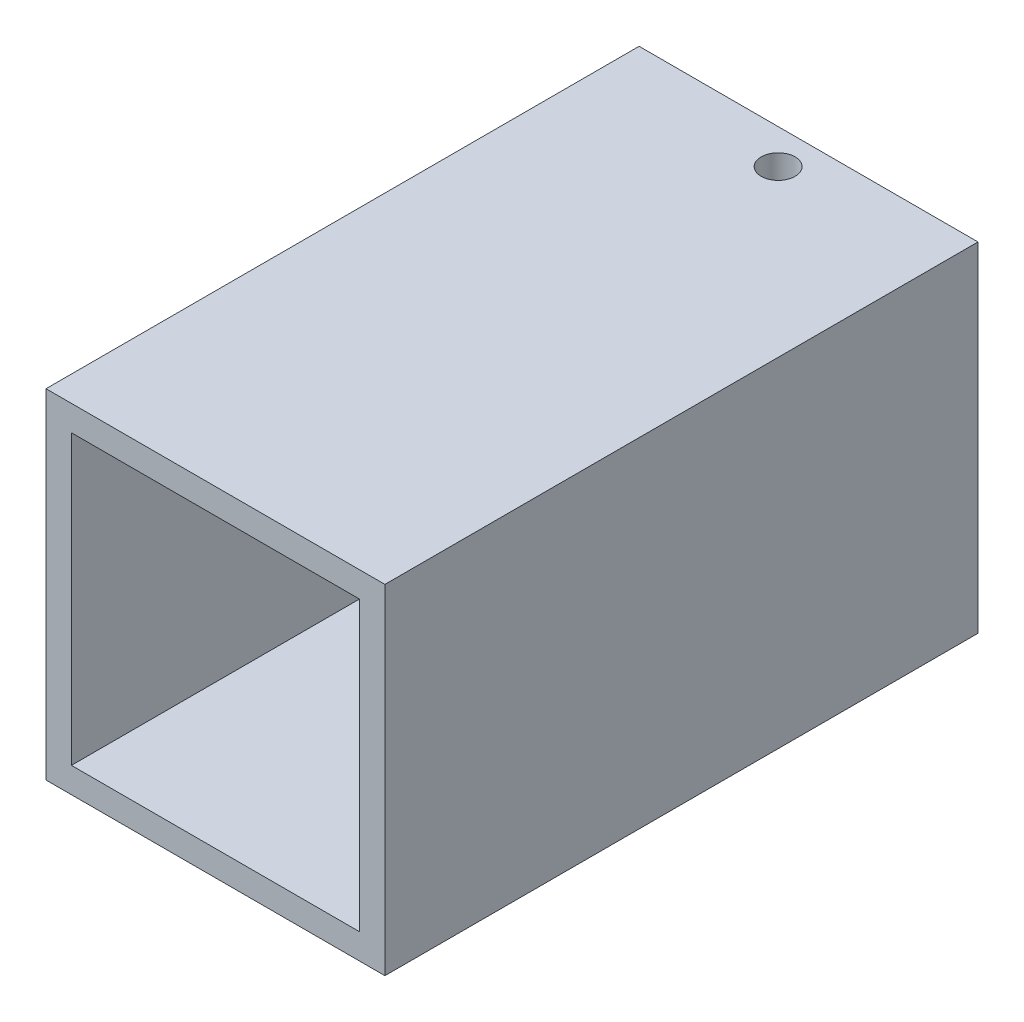
SolidWorks part; units mm, degrees
ref_plane "Płaszczyzna przednia" through (0, 0, 0) normal (0, 0, 1) x (1, 0, 0)
ref_plane "Płaszczyzna górna" through (0, 0, 0) normal (0, 1, 0) x (1, 0, 0)
ref_plane "Płaszczyzna prawa" through (0, 0, 0) normal (1, 0, 0) x (0, 0, -1)
sketch "Szkic1" plane through (0, 0, 0) normal (0, 0, 1) x (1, 0, 0)
  line L2 (-30.423, 18.5) -> (-30.423, -1.5)
  line L3 (-30.423, -1.5) -> (-10.423, -1.5)
  line L4 (-10.423, 18.5) -> (-10.423, -1.5)
  line L8 (-30.423, 18.5) -> (-10.423, 18.5)
  line L10 (-28.923, 17) -> (-11.923, 17)
  line L11 (-28.923, 17) -> (-28.923, 0)
  line L12 (-28.923, 0) -> (-11.923, 0)
  line L13 (-11.923, 17) -> (-11.923, 0)
  dimension "D1" = 20
  dimension "D2" = 20
  dimension "D3" = 1.5
  dimension "D4" = 1.5
  dimension "D5" = 1.5
  dimension "D6" = 1.5
extrude "Dodanie-wyciągnięcie1" add sketch "Szkic1" along normal blind 35
sketch "Szkic3" plane through (0, 18.5, 0) normal (0, 1, 0) x (1, 0, 0)
  circle A0 centre (-20.1716, -2.0464) radius 1
extrude "Wytnij-wyciągnięcie1" cut sketch "Szkic3" against normal through all
